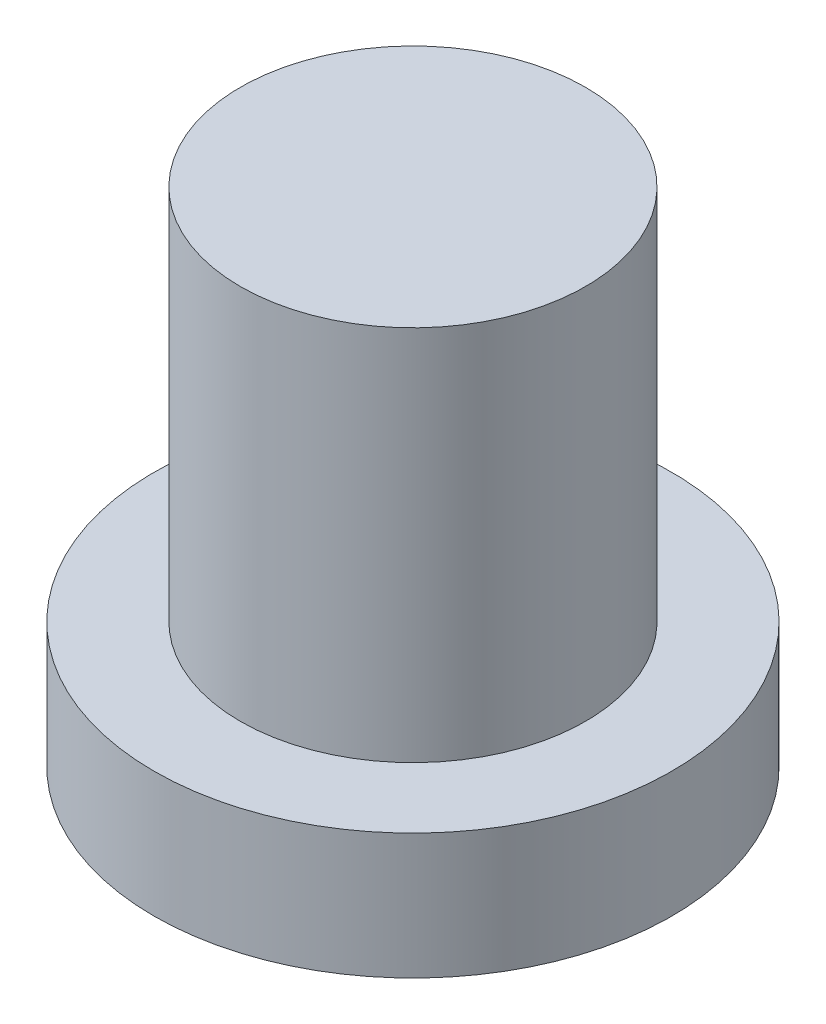
SolidWorks part; units mm, degrees
ref_plane "Front Plane" through (0, 0, 0) normal (0, 0, 1) x (1, 0, 0)
ref_plane "Top Plane" through (0, 0, 0) normal (0, 1, 0) x (1, 0, 0)
ref_plane "Right Plane" through (0, 0, 0) normal (1, 0, 0) x (0, 0, -1)
sketch "Sketch2" plane through (0, 0, 0) normal (0, 1, 0) x (1, 0, 0)
  circle A0 centre (0, 0) radius 2.0625
extrude "Boss-Extrude1" add sketch "Sketch2" along normal blind 1
sketch "Sketch3" plane through (0, 1, 0) normal (0, 1, 0) x (1, 0, 0)
  circle A0 centre (0, 0) radius 1.375
extrude "Boss-Extrude2" add sketch "Sketch3" along normal blind 3
